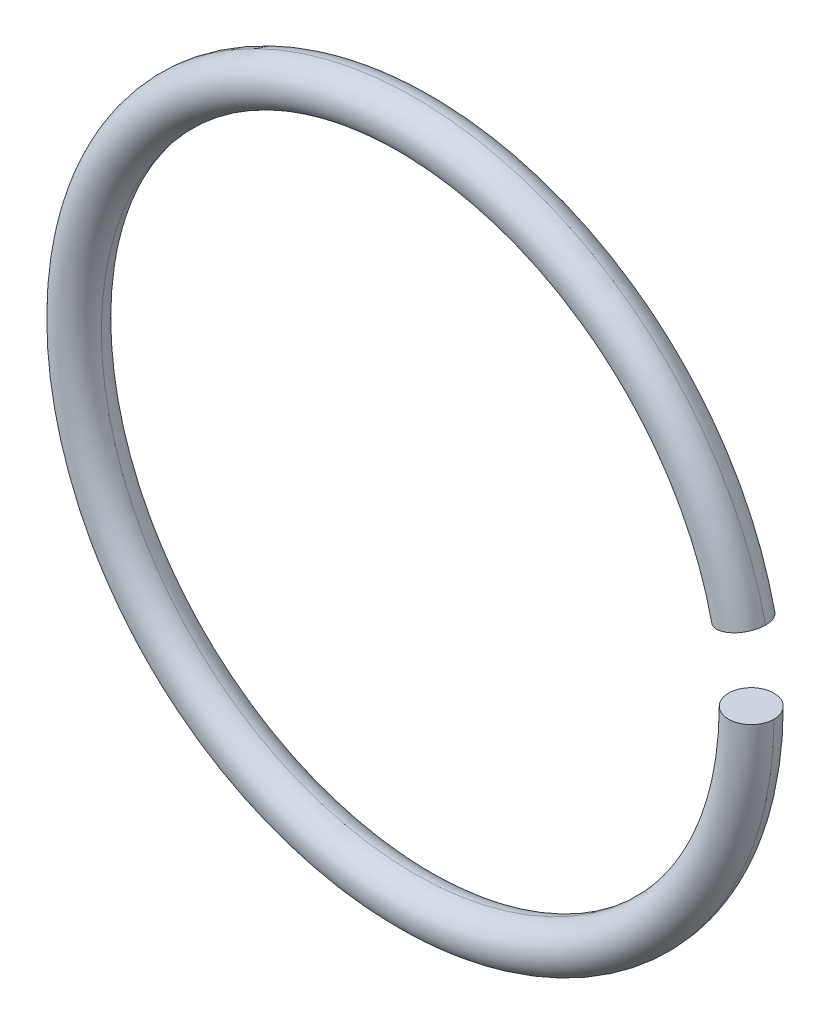
SolidWorks part; units mm, degrees
ref_plane "Front" through (0, 0, 0) normal (0, 0, 1) x (1, 0, 0)
ref_plane "Top" through (0, 0, 0) normal (0, 1, 0) x (1, 0, 0)
ref_plane "Right" through (0, 0, 0) normal (1, 0, 0) x (0, 0, -1)
sketch "Sketch1" plane through (0, 0, 0) normal (0, 0, 1) x (1, 0, 0)
  line L0 (-76.5339, 0) -> (24.9274, 0) construction
  line L1 (0, 65.6634) -> (0, -53.6178) construction
  line L2 (0, 0) -> (15.1749, 3.3461) construction
  arc A0 (13.5251, 2.9824) -> (13.85, 0) centre (0, 0) ccw
  dimension "d2" = 27.7
  dimension "e" = 3
sketch "Sketch2" plane through (0, 0, 0) normal (0, 1, 0) x (1, 0, 0)
  circle A0 centre (14.85, 0) radius 1
  point P2 (13.85, 0)
  dimension "d4" = 2
sweep "Sweep1" add profiles "Sketch2" path "Sketch1"
split line "Split Line3"
